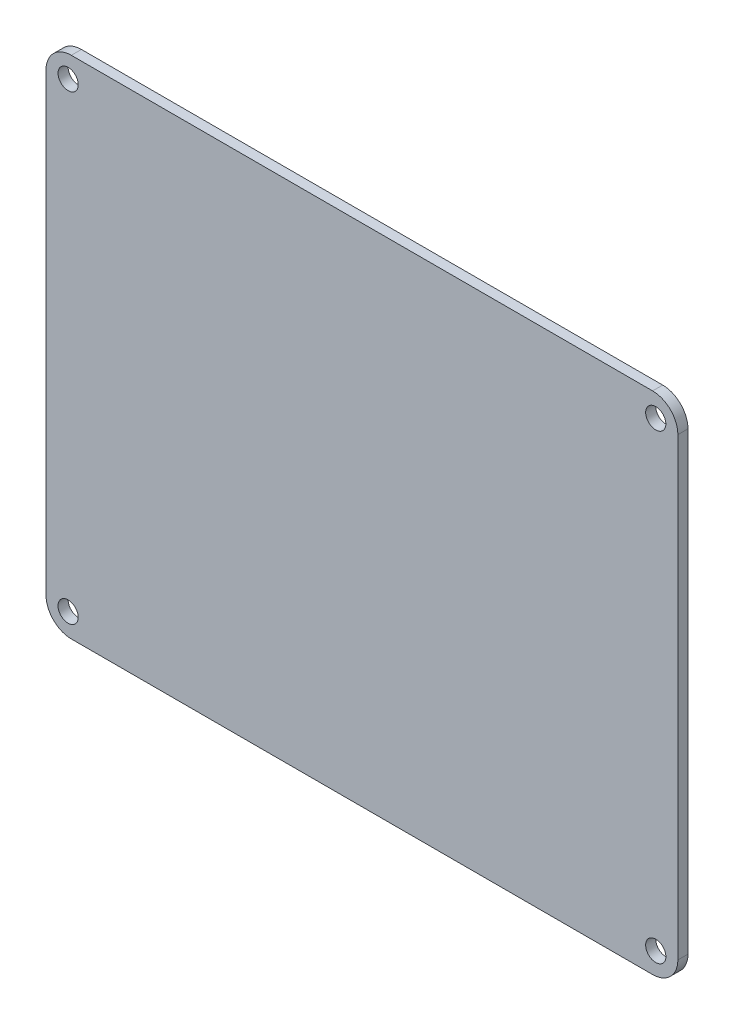
SolidWorks part; units mm, degrees
ref_plane "Front Plane" through (0, 0, 0) normal (0, 0, 1) x (1, 0, 0)
ref_plane "Top Plane" through (0, 0, 0) normal (0, 1, 0) x (1, 0, 0)
ref_plane "Right Plane" through (0, 0, 0) normal (1, 0, 0) x (0, 0, -1)
sketch "Sketch1" plane through (0, 0, 0) normal (0, 0, 1) x (1, 0, 0)
  line L0 (0, 0) -> (-46.5, 0) construction
  line L1 (46, -40) -> (-46, -40)
  line L2 (50, -36) -> (50, 36)
  line L3 (46, 40) -> (-46, 40)
  line L4 (-50, -36) -> (-50, 36)
  line L5 (50, -40) -> (-50, 40) construction
  line L6 (50, 40) -> (-50, -40) construction
  line L7 (-46.5, 0) -> (-46.5, 36.5) construction
  line L8 (-46.5, 0) -> (-46.5, -36.5) construction
  line L9 (-46.5, -36.5) -> (46.5, -36.5) construction
  line L10 (46.5, 0) -> (46.5, 36.5) construction
  line L11 (0, 0) -> (46.5, 0) construction
  line L12 (-46.5, 36.5) -> (46.5, 36.5) construction
  circle A0 centre (-46.5, 36.5) radius 1.6
  circle A1 centre (-46.5, -36.5) radius 1.6
  circle A2 centre (46.5, -36.5) radius 1.6
  arc A4 (-46, -40) -> (-50, -36) centre (-46, -36) cw
  arc A5 (-50, 36) -> (-46, 40) centre (-46, 36) cw
  arc A6 (50, 36) -> (46, 40) centre (46, 36) ccw
  arc A7 (46, -40) -> (50, -36) centre (46, -36) ccw
  circle A8 centre (46.5, 36.5) radius 1.6
  point P0 (0, 0)
  dimension "D5" = 3.2
  dimension "D7" = 3.2
  dimension "D9" = 46.5
  dimension "D10" = 3.2
  dimension "D11" = 4
  dimension "D13" = 3.2
  dimension "D1" = 100
  dimension "D2" = 80
  dimension "D3" = 46.5
  dimension "D4" = 36.5
  dimension "D6" = 36.5
  dimension "D8" = 93
  dimension "D12" = 36.5
extrude "Boss-Extrude1" add sketch "Sketch1" along normal blind 1.6
